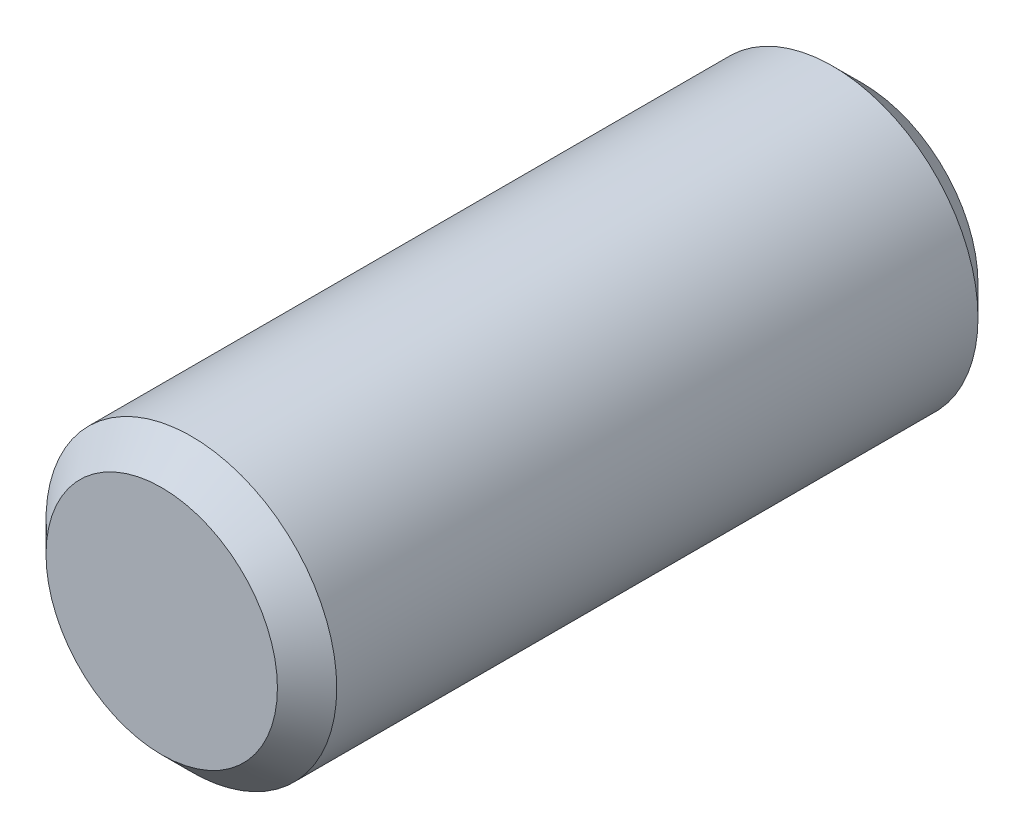
SolidWorks part; units mm, degrees
ref_plane "Front Plane" through (0, 0, 0) normal (0, 0, 1) x (1, 0, 0)
ref_plane "Top Plane" through (0, 0, 0) normal (0, 1, 0) x (1, 0, 0)
ref_plane "Right Plane" through (0, 0, 0) normal (1, 0, 0) x (0, 0, -1)
sketch "Sketch1" plane through (0, 0, 0) normal (0, 0, 1) x (1, 0, 0)
  circle A0 centre (0, 0) radius 2.49
  dimension "D1" = 4.98
extrude "Extrude1" add sketch "Sketch1" along normal blind 12
chamfer "Chamfer1" distance 0.508 angle 45 2 edges at (2.49, 0, 0) (2.49, 0, 12)
